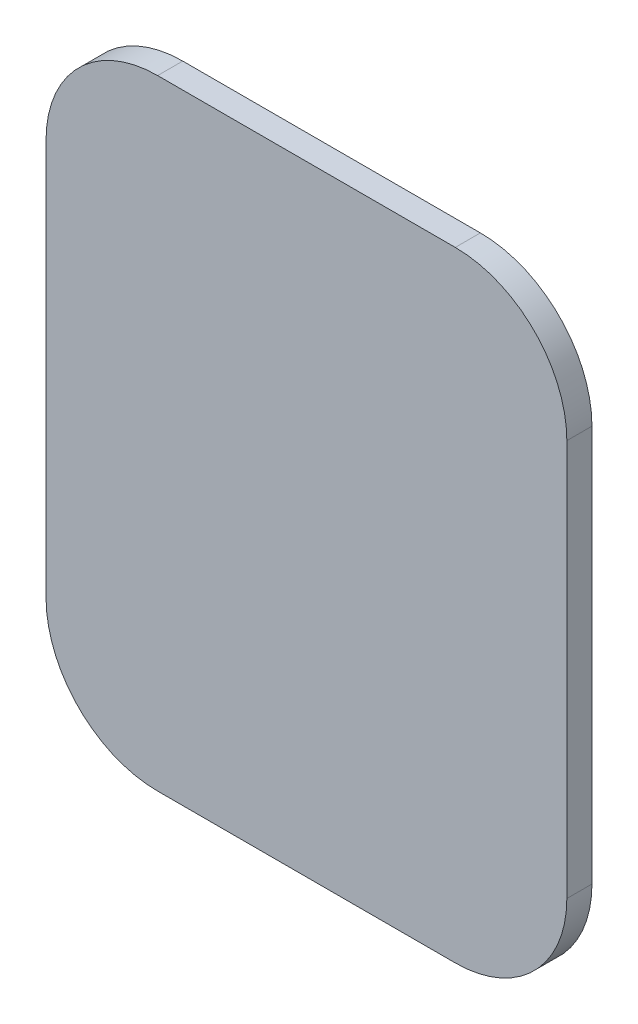
SolidWorks part; units mm, degrees
ref_plane "前视基准面" through (0, 0, 0) normal (0, 0, 1) x (1, 0, 0)
ref_plane "上视基准面" through (0, 0, 0) normal (0, 1, 0) x (1, 0, 0)
ref_plane "右视基准面" through (0, 0, 0) normal (1, 0, 0) x (0, 0, -1)
other "Configuration Table"
sketch "草图2" plane through (0, 0, 0) normal (0, 0, 1) x (1, 0, 0)
  line L1 (-18.67, 22.215) -> (18.67, 22.215)
  line L2 (-18.67, 22.215) -> (-18.67, -22.215)
  line L3 (-18.67, -22.215) -> (18.67, -22.215)
  line L4 (18.67, 22.215) -> (18.67, -22.215)
  line L5 (0, -22.215) -> (0, 22.215) construction
  line L6 (-18.67, 0) -> (18.67, 0) construction
  point P0 (0, 0)
  dimension "D1" = 37.34
  dimension "D2" = 44.43
extrude "凸台-拉伸1" add sketch "草图2" along normal blind 1.8
sketch "草图4" plane through (0, 0, 0) normal (0, 0, -1) x (-1, 0, 0)
  line L0 (0, 17.5) -> (0, 0)
  line L1 (-15.5, 17.5) -> (15.5, 17.5)
  line L2 (-15.5, 17.5) -> (-15.5, -17.5)
  line L3 (-15.5, -17.5) -> (15.5, -17.5)
  line L4 (15.5, 17.5) -> (15.5, -17.5)
  line L5 (0, -17.5) -> (0, 17.5) construction
  line L6 (-15.5, 0) -> (15.5, 0) construction
  point P0 (0, 0)
  point P4 (0, 0)
  dimension "D1" = 31
  dimension "D2" = 35
extrude "凸台-拉伸3" add sketch "草图4" along normal blind 1.89 contours L2 L1 L4 L3
fillet "圆角1" radius 8 4 edges at (-18.67, 22.215, 0.9) (18.67, 22.215, 0.9) (18.67, -22.215, 0.9) (-18.67, -22.215, 0.9)
fillet "圆角2" radius 8 4 edges at (15.5, -17.5, -0.945) (-15.5, -17.5, -0.945) (-15.5, 17.5, -0.945) (15.5, 17.5, -0.945)
